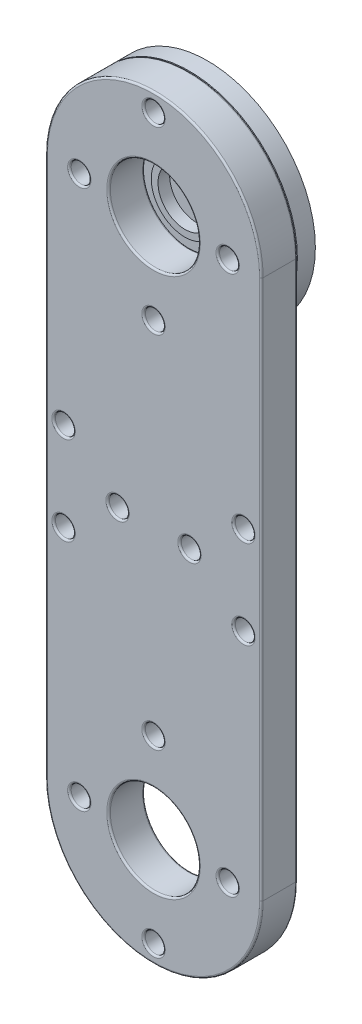
SolidWorks part; units mm, degrees
material "Полибутадиен (PB)"
ref_plane "Спереди" through (0, 0, 0) normal (0, 0, 1) x (1, 0, 0)
ref_plane "Сверху" through (0, 0, 0) normal (0, 1, 0) x (1, 0, 0)
ref_plane "Справа" through (0, 0, 0) normal (1, 0, 0) x (0, 0, -1)
sketch "Эскиз1" plane through (0, 0, 0) normal (1, 0, 0) x (0, 0, -1)
  line L0 (0, 3.75) -> (0, 12)
  line L1 (0, 12) -> (2, 12)
  line L2 (2, 12) -> (2, 4.5)
  line L3 (2, 4.5) -> (4.5, 4.5)
  line L4 (4.5, 4.5) -> (4.5, 3)
  line L5 (4.5, 3) -> (1.5, 3)
  line L6 (-0.5, 3.75) -> (0, 3.75)
  line L7 (-0.5, 3.75) -> (-0.5, 3)
  line L8 (-0.5, 3) -> (0.8, 3)
  line L9 (0.8, 3) -> (0.8, 1.4)
  line L10 (0.8, 1.4) -> (1.5, 1.4)
  line L11 (1.5, 3) -> (1.5, 1.4)
  dimension "D1" = 2
  dimension "D2" = 3
  dimension "D3" = 12
  dimension "D4" = 4.5
  dimension "D5" = 3
  dimension "D6" = 3.75
  dimension "D7" = 3
  dimension "D8" = 0.5
  dimension "D9" = 4.5
  dimension "D10" = 1.3
  dimension "D11" = 1.4
ref_axis "Ось1" through (0, 0, 50) along (0, 0, -1)
revolve "Повернуть1" add sketch "Эскиз1" angle 360 about axis through (0, 0, 50) along (0, 0, -1)
sketch "Эскиз2" plane through (0, 0, 0) normal (0, 0, 1) x (1, 0, 0)
  line L0 (0, 0) -> (8.25, 0) construction
  line L1 (0, 0) -> (7.7525, -2.8217) construction
  line L2 (0, 0) -> (0, 7) construction
  line L3 (0, 0) -> (2.3941, 6.5778) construction
  line L4 (0, 0) -> (0, 7) construction
  line L5 (0, 0) -> (-2.3941, 6.5778) construction
  circle A0 centre (8.25, 0) radius 0.75
  circle A1 centre (7.7525, -2.8217) radius 0.75
  circle A2 centre (7.7525, 2.8217) radius 0.75
  circle A3 centre (-8.25, 0) radius 0.75
  circle A4 centre (-7.7525, -2.8217) radius 0.75
  circle A5 centre (-7.7525, 2.8217) radius 0.75
  circle A6 centre (0, 7) radius 0.75
  circle A8 centre (0, 10) radius 0.75
  circle A9 centre (2.3941, 6.5778) radius 0.75
  circle A10 centre (3.4202, 9.3969) radius 0.75
  circle A11 centre (-2.3941, 6.5778) radius 0.75
  circle A12 centre (-3.4202, 9.3969) radius 0.75
  circle A13 centre (0, -7) radius 0.75
  circle A14 centre (0, -10) radius 0.75
  circle A15 centre (3.4202, -9.3969) radius 0.75
  circle A16 centre (2.3941, -6.5778) radius 0.75
  circle A17 centre (-2.3941, -6.5778) radius 0.75
  circle A18 centre (-3.4202, -9.3969) radius 0.75
  point P12 (0, 0)
  point P20 (0, 0)
  point P51 (0, 0)
  dimension "D1" = 1.5
  dimension "D7" = 1.5
  dimension "D9" = 1.5
  dimension "D2" = 8.25
  dimension "D4" = 20
  dimension "D8" = 7
  dimension "D10" = 10
  dimension "D12" = 20
  dimension "D14" = 20
  dimension "D3" = 2
  dimension "D5" = 2
  dimension "D6" = 2
  dimension "D11" = 2
  dimension "D13" = 2
  dimension "D15" = 2
extrude "Вырез-Вытянуть1" cut sketch "Эскиз2" against normal through all
sketch "스케치1" plane through (0, 0, 0) normal (0, 0, 1) x (1, 0, 0)
  line L0 (-12, 0) -> (-12, -60)
  line L1 (-12, -30) -> (12, -30) construction
  line L2 (12, -60) -> (12, 0)
  circle A0 centre (0, 0) radius 5
  circle A1 centre (0, 0) radius 12
  arc A2 (12, 0) -> (-12, 0) centre (0, 0) ccw
  circle A3 centre (-8.25, 0) radius 0.75 construction
  circle A4 centre (0, -10) radius 0.75 construction
  circle A5 centre (8.25, 0) radius 0.75 construction
  circle A6 centre (0, 10) radius 0.75 construction
  circle A7 centre (-8.25, 0) radius 0.75 construction
  circle A8 centre (0, -10) radius 0.75 construction
  circle A9 centre (8.25, 0) radius 0.75 construction
  circle A10 centre (0, 10) radius 0.75 construction
  arc A15 (12, -60) -> (-12, -60) centre (0, -60) cw
  circle A16 centre (0, -60) radius 5
  circle A17 centre (-8.25, 0) radius 1.1
  circle A18 centre (0, 10) radius 1.1
  circle A19 centre (8.25, 0) radius 1.1
  circle A20 centre (0, -10) radius 1.1
  circle A21 centre (0, -50) radius 1.1
  circle A22 centre (0, -50) radius 0.75 construction
  circle A23 centre (8.25, -60) radius 1.1
  circle A24 centre (8.25, -60) radius 0.75 construction
  circle A25 centre (-8.25, -60) radius 1.1
  circle A26 centre (-8.25, -60) radius 0.75 construction
  circle A27 centre (0, -70) radius 1.1
  circle A28 centre (0, -70) radius 0.75 construction
  circle M7 centre (3.4202, -9.3969) radius 0.75
  circle M8 centre (2.3941, -6.5778) radius 0.75
  circle M9 centre (-3.4202, -9.3969) radius 0.75
  circle M10 centre (-2.3941, -6.5778) radius 0.75
  circle M12 centre (0, -7) radius 0.75
  circle M13 centre (-3.4202, 9.3969) radius 0.75
  circle M14 centre (-2.3941, 6.5778) radius 0.75
  circle M15 centre (3.4202, 9.3969) radius 0.75
  circle M16 centre (2.3941, 6.5778) radius 0.75
  circle M18 centre (-7.7525, -2.8217) radius 0.75
  circle M19 centre (-7.7525, 2.8217) radius 0.75
  circle M21 centre (7.7525, 2.8217) radius 0.75
  circle M22 centre (0, 7) radius 0.75
  circle M23 centre (7.7525, -2.8217) radius 0.75
  circle M25 centre (0, 0) radius 12
  dimension "D3" = 10
  dimension "D4" = 2.2
  dimension "D2" = 30
  dimension "D1" = 0
extrude "보스-돌출1" add sketch "스케치1" along normal blind 4 separate body contours A15 L2 L0 A25 A21 A16 A23 A27 M25 | A20 A19 A18 A17 A0 M25 M8 M10 M12 M14 M16 M18 M22 M23 M21 M19 M15 M13 M9 M7 | M13 | M14 | M22 | M16 | M15 | M21 | M23 | M18 | M19 | M10 | M9 | M12 | M8 | M7
sketch "스케치2" plane through (0, 0, 0) normal (0, 0, -1) x (-1, 0, 0)
  line L1 (-12, -30) -> (40.626, -30) construction
  line L2 (-12, -60) -> (-12, 0) construction
  line L3 (0, 0) -> (0, -60) construction
  line L5 (12, -60) -> (12, 0)
  line L6 (-12, 0) -> (-12, -60)
  line L7 (12, -34.9201) -> (12, -25.0799)
  line L8 (-12, -25.0799) -> (-12, -34.9201)
  arc A0 (9.2593, -36.7779) -> (-9.2593, -36.7779) centre (0, -60) ccw
  arc A1 (-9.2593, -23.2221) -> (9.2593, -23.2221) centre (0, 0) ccw
  arc A2 (9.2593, -36.7779) -> (12, -34.9201) centre (10, -34.9201) ccw
  arc A3 (-9.2593, -36.7779) -> (-12, -34.9201) centre (-10, -34.9201) cw
  arc A4 (-12, -60) -> (12, -60) centre (0, -60) ccw
  arc A5 (12, 0) -> (-12, 0) centre (0, 0) ccw
  arc A8 (9.2593, -23.2221) -> (12, -25.0799) centre (10, -25.0799) cw
  arc A9 (-9.2593, -23.2221) -> (-12, -25.0799) centre (-10, -25.0799) ccw
  circle A10 centre (-10, -25.0799) radius 0.95
  circle A11 centre (-10, -34.9201) radius 0.95
  circle A12 centre (10, -25.0799) radius 0.95
  circle A13 centre (10, -34.9201) radius 0.95
  circle A15 centre (-4, -30) radius 0.95
  circle A16 centre (4, -30) radius 0.95
  circle A17 centre (-10, -25.0799) radius 1.1
  circle A18 centre (-4, -30) radius 1.1
  circle A19 centre (4, -30) radius 1.1
  circle A20 centre (10, -25.0799) radius 1.1
  circle A21 centre (10, -34.9201) radius 1.1
  circle A22 centre (-10, -34.9201) radius 1.1
  dimension "D1" = 50
  dimension "D3" = 2
  dimension "D4" = 1.9
  dimension "D5" = 8
  dimension "D6" = 2.2
  dimension "D2" = 0
extrude "컷-돌출1" cut sketch "스케치2" against normal through all contours A10 | A17 A10 | A11 | A22 A11 | A15 | A18 A15 | A16 | A19 A16 | A12 | A20 A12 | A13 | A21 A13 | A1 A8 L7 A2 A0 A3 L8 A9
fillet "필렛1" radius 0.2 40 edges at (5, 0, 0) (-7.15, 0, 0) (1.1, 10, 0) (9.35, 0, 0) (1.1, -10, 0) (1.1, -70, 0) (9.35, -60, 0) (5, -60, 0) (12, -30, 0) (0, 12, 0) (-12, -30, 0) (0, -72, 0) (1.1, -50, 0) (-7.15, -60, 0) (8.9, -25.0799, 0) (-11.1, -34.9201, 0) (-11.1, -25.0799, 0) (-5.1, -30, 0) (2.9, -30, 0) (8.9, -34.9201, 0) (5, 0, 4) (-7.15, 0, 4) (1.1, 10, 4) (9.35, 0, 4) (1.1, -10, 4) (1.1, -70, 4) (9.35, -60, 4) (5, -60, 4) (-12, -30, 4) (0, 12, 4) (12, -30, 4) (0, -72, 4) (1.1, -50, 4) (-7.15, -60, 4) (8.9, -25.0799, 4) (-11.1, -34.9201, 4) (-11.1, -25.0799, 4) (-5.1, -30, 4) (2.9, -30, 4) (8.9, -34.9201, 4)
